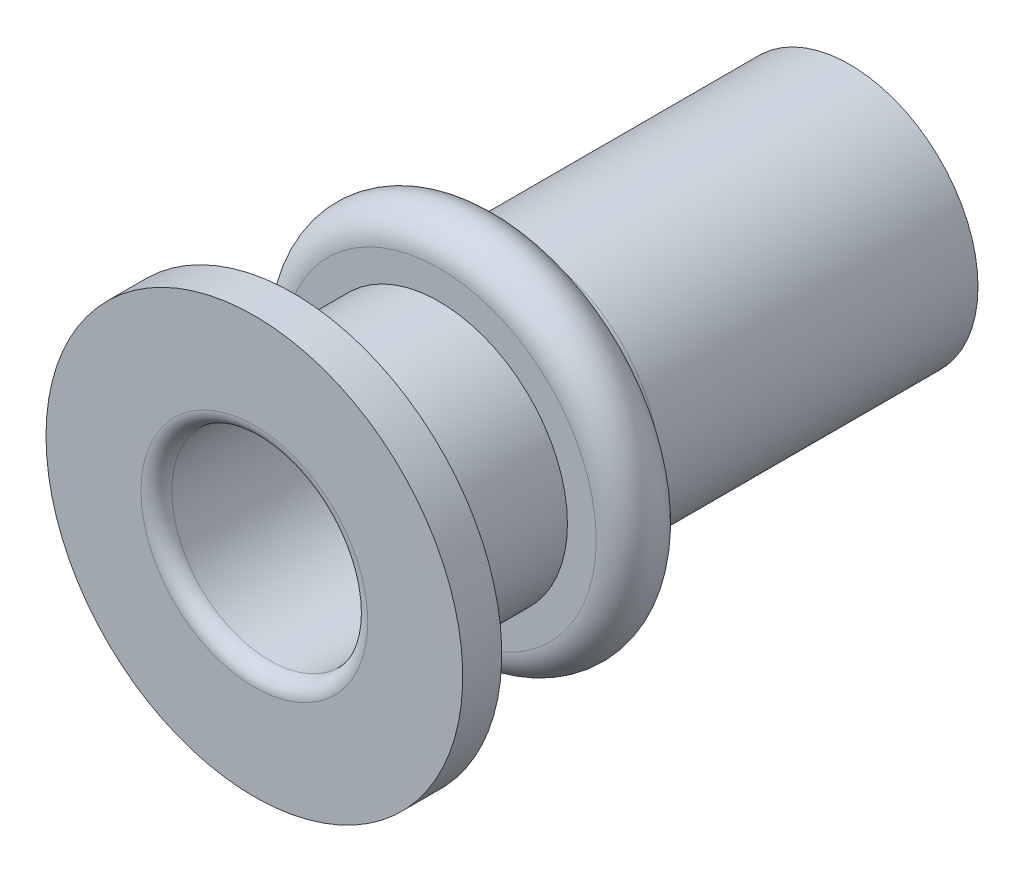
SolidWorks part; units mm, degrees
material "ASTM A36 Steel"
ref_plane "Front Plane" through (0, 0, 0) normal (0, 0, 1) x (1, 0, 0)
ref_plane "Top Plane" through (0, 0, 0) normal (0, 1, 0) x (1, 0, 0)
ref_plane "Right Plane" through (0, 0, 0) normal (1, 0, 0) x (0, 0, -1)
sketch "Sketch1" plane through (0, 0, 0) normal (1, 0, 0) x (0, 0, -1)
  line L0 (-2.825, 0) -> (-7.0323, 0) construction
  line L1 (0, 2.8067) -> (0, 5.1562)
  line L2 (0, 5.1562) -> (0.9652, 5.1562)
  line L3 (0.9652, 5.1562) -> (0.9652, 3.175)
  line L4 (0.9652, 3.175) -> (4.572, 3.175)
  line L5 (4.572, 3.175) -> (4.572, 3.8862)
  line L6 (6.096, 3.8862) -> (6.096, 3.937)
  line L7 (0.381, 2.4257) -> (6.858, 2.4257)
  line L8 (6.858, 2.4257) -> (7.0926, 2.0193)
  line L9 (7.0926, 2.0193) -> (14.4974, 2.0193)
  line L10 (14.4974, 2.0193) -> (14.732, 2.4257)
  line L11 (14.732, 2.4257) -> (14.732, 3.175)
  line L12 (14.732, 3.175) -> (6.858, 3.175)
  arc A0 (4.572, 3.8862) -> (6.096, 3.8862) centre (5.334, 3.8862) cw
  arc A1 (6.858, 3.175) -> (6.096, 3.937) centre (6.858, 3.937) cw
  arc A2 (0, 2.8067) -> (0.381, 2.4257) centre (0.381, 2.8067) ccw
  point P19 (2.286, 3.175)
  dimension "D15" = 0.381
  dimension "D1" = 4.0386
  dimension "D2" = 4.8514
  dimension "D3" = 10.3124
  dimension "D4" = 0.9652
  dimension "D5" = 3.6068
  dimension "D6" = 1.524
  dimension "D7" = 0.508
  dimension "D8" = 6.35
  dimension "D9" = 60
  dimension "D10" = 60
  dimension "D11" = 13.7668
  dimension "D12" = 10.16
  dimension "D13" = 2.286
  dimension "D14" = 2.286
revolve "Revolve1" add sketch "Sketch1" angle 360 about L0
